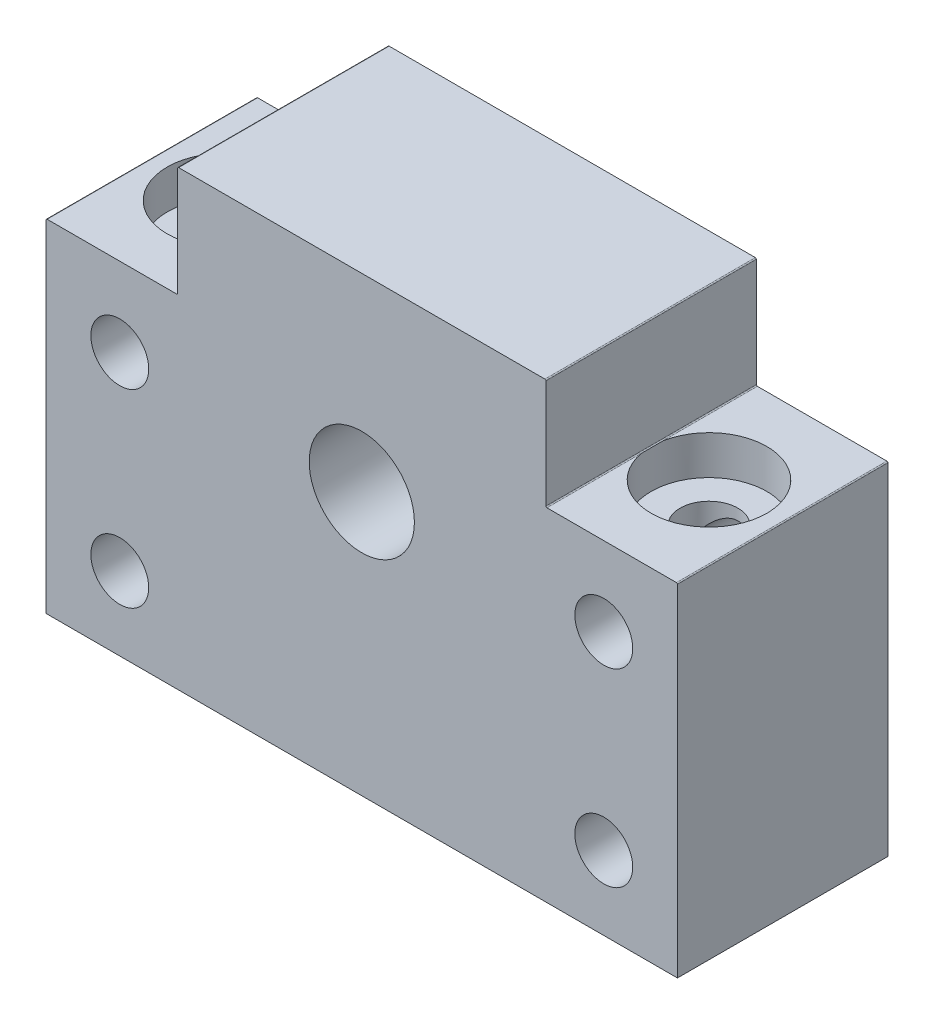
SolidWorks part; units mm, degrees
ref_plane "정면" through (0, 0, 0) normal (0, 0, 1) x (1, 0, 0)
ref_plane "윗면" through (0, 0, 0) normal (0, 1, 0) x (1, 0, 0)
ref_plane "우측면" through (0, 0, 0) normal (1, 0, 0) x (0, 0, -1)
sketch "스케치1" plane through (0, 0, 0) normal (0, 0, 1) x (1, 0, 0)
  line L1 (-30, 16.25) -> (30, 16.25)
  line L2 (-30, 16.25) -> (-30, -16.25)
  line L3 (-30, -16.25) -> (30, -16.25)
  line L4 (30, 16.25) -> (30, -16.25)
  line L5 (-30, 16.25) -> (30, -16.25) construction
  line L6 (-30, -16.25) -> (30, 16.25) construction
  point P0 (0, 0)
  dimension "D1" = 60
  dimension "D2" = 32.5
extrude "보스-돌출1" add sketch "스케치1" along normal blind 20
sketch "스케치2" plane through (0, 16.25, 0) normal (0, 1, 0) x (1, 0, 0)
  line L0 (30, -20) -> (-30, -20) construction
  line L1 (-17.5, 0) -> (17.5, 0)
  line L2 (-17.5, 0) -> (-17.5, -20)
  line L3 (-17.5, -20) -> (17.5, -20)
  line L4 (17.5, 0) -> (17.5, -20)
  line L5 (-17.5, 0) -> (17.5, -20) construction
  line L6 (-17.5, -20) -> (17.5, 0) construction
  line L7 (30, 0) -> (-30, 0) construction
  point P0 (0, -10)
  dimension "D1" = 0
  dimension "D2" = 35
  dimension "D3" = 0
extrude "보스-돌출2" add sketch "스케치2" along normal blind 10.5
fillet "필렛1" radius 0.1 6 edges at (-17.5, 16.25, 10) (17.5, 16.25, 10) (30, 16.25, 10) (-30, 16.25, 10) (-17.5, 26.75, 10) (17.5, 26.75, 10)
sketch "스케치3" plane through (0, 0, 20) normal (0, 0, 1) x (1, 0, 0)
  line L0 (-30, -16.25) -> (30, -16.25) construction
  circle A0 centre (0, 8.75) radius 5
  circle A1 centre (-23, 8.75) radius 2.75
  circle A2 centre (-23, -9.25) radius 2.75
  circle A3 centre (23, 8.75) radius 2.75
  circle A4 centre (23, -9.25) radius 2.75
  dimension "D2" = 10
  dimension "D5" = 5.5
  dimension "D6" = 5.5
  dimension "D7" = 5.5
  dimension "D8" = 5.5
  dimension "D1" = 25
  dimension "D3" = 25
  dimension "D4" = 18
  dimension "D9" = 23
  dimension "D10" = 0
  dimension "D11" = 23
  dimension "D12" = 23
  dimension "D13" = 23
  dimension "D14" = 25
  dimension "D15" = 18
extrude "컷-돌출1" cut sketch "스케치3" against normal through all
hole_wizard "M5 남비 머리 나사용 카운터보어1" positions "스케치6" profile "스케치7" counterbore size "M5" standard "ISO"
sketch "스케치6" plane through (0, 16.25, 0) normal (0, 1, 0) x (1, 0, 0)
  line L2 (-17.6, 0) -> (-29.9, 0) construction
  line L3 (29.9, 0) -> (17.6, 0) construction
  point P0 (23, -10)
  point P3 (-23, -10)
  dimension "D1" = 46
  dimension "D2" = 23
  dimension "D3" = 10
  dimension "D4" = 10
sketch "스케치7" plane through (23, 16.25, 10) normal (1, 0, 0) x (0, 0, 1)
  line L0 (0, 0) -> (0, 41.6524)
  line L1 (0, 41.6524) -> (2.75, 40)
  line L2 (2.75, 40) -> (2.75, 3.7)
  line L3 (2.75, 3.7) -> (5.5, 3.7)
  line L4 (5.5, 3.7) -> (5.5, 0)
  line L5 (5.5, 0) -> (0, 0)
  line L10 (0, 41.6524) -> (-2.75, 40) construction
  line L11 (0, -6.35) -> (0, 107.95) construction
  dimension "구멍 지름" = 5.5
  dimension "구멍 깊이" = 40
  dimension "카운터보어 지름" = 11
  dimension "카운터보어 깊이" = 3.7
  dimension "드릴 각도" = 118
